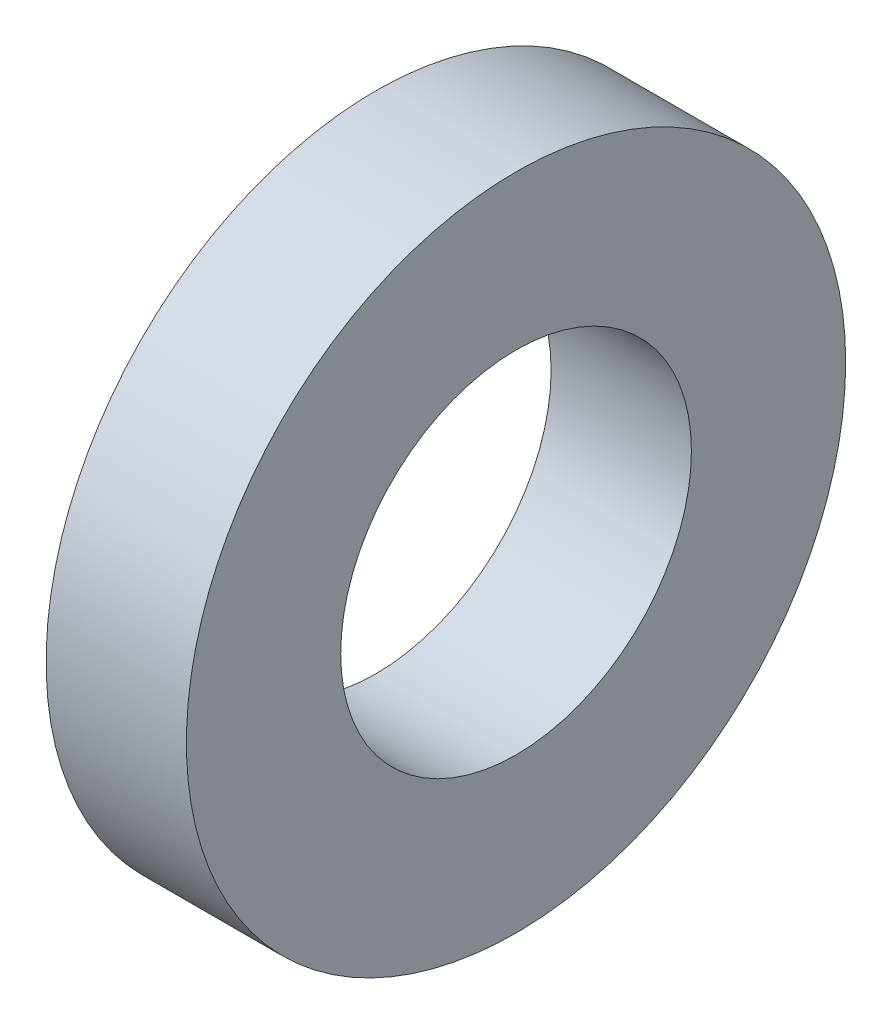
SolidWorks part; units mm, degrees
ref_plane "Front Plane" through (0, 0, 0) normal (1, 0, 0) x (0, 1, 0)
ref_plane "Top Plane" through (0, 0, 0) normal (0, 0, 1) x (0, 1, 0)
ref_plane "Right Plane" through (0, 0, 0) normal (0, 1, 0) x (-1, 0, 0)
sketch "Sketch1" plane through (0, 0, 0) normal (1, 0, 0) x (0, 1, 0)
  circle A0 centre (0, 0) radius 12.5
  circle A1 centre (0, 0) radius 23.5
  dimension "D1" = 25
  dimension "D2" = 47
extrude "Boss-Extrude1" add sketch "Sketch1" along normal blind 10
